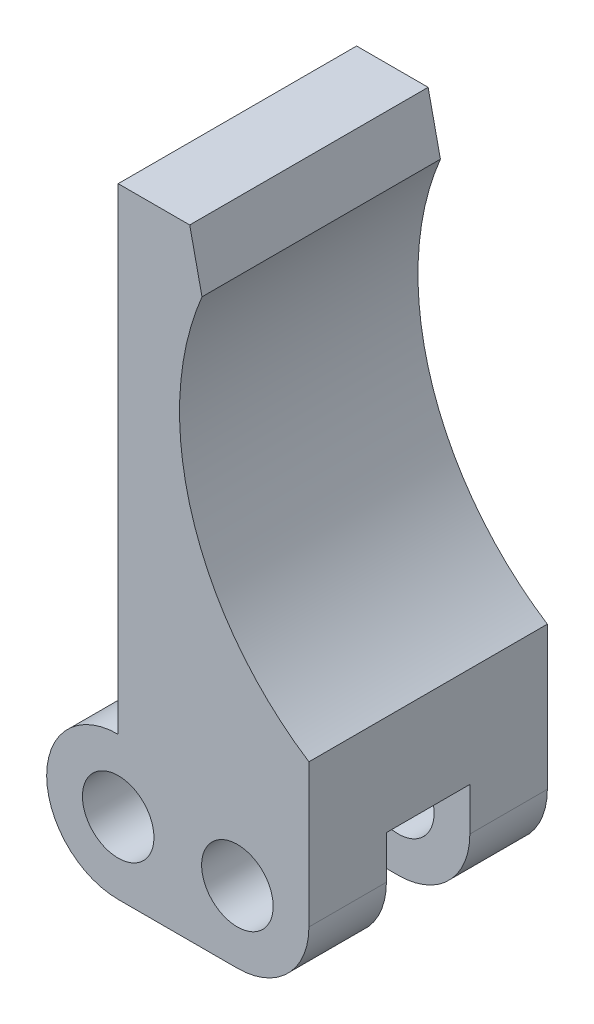
SolidWorks part; units mm, degrees
material "ABS"
ref_plane "Front Plane" through (0, 0, 0) normal (0, 0, 1) x (1, 0, 0)
ref_plane "Top Plane" through (0, 0, 0) normal (0, 1, 0) x (1, 0, 0)
ref_plane "Right Plane" through (0, 0, 0) normal (1, 0, 0) x (0, 0, -1)
sketch "Sketch1" plane through (0, 0, 0) normal (0, 0, 1) x (1, 0, 0)
  line L0 (0, -3) -> (5, -3)
  line L2 (0, 3) -> (0, 23)
  line L3 (8, 0) -> (8, 6)
  line L4 (0, 23) -> (3, 23)
  line L5 (3, 23) -> (3.5153, 20.6462)
  arc A0 (0, 3) -> (0, -3) centre (0, 0) ccw
  arc A1 (5, -3) -> (8, 0) centre (5, 0) ccw
  arc A2 (8, 6) -> (3.5153, 20.6462) centre (14.5, 16) cw
  circle A4 centre (0, 0) radius 1.5
  circle A5 centre (5, 0) radius 1.5
  dimension "D1" = 6
  dimension "D4" = 3
  dimension "D6" = 6
  dimension "D8" = 14.5
  dimension "D9" = 2.3538
  dimension "D2" = 20
  dimension "D3" = 3
  dimension "D5" = 5
  dimension "D7" = 16
extrude "Boss-Extrude1" add sketch "Sketch1" along normal mid plane 10
sketch "Sketch2" plane through (0, 0, 0) normal (0, 0, 1) x (1, 0, 0)
  line L0 (0, 3.5) -> (5, 3.5)
  line L3 (0, -3.5) -> (5, -3.5)
  circle A0 centre (0, 0) radius 1.5
  arc A1 (0, 3.5) -> (0, -3.5) centre (0, 0) ccw
  circle A2 centre (5, 0) radius 1.5
  arc A3 (5, -3.5) -> (5, 3.5) centre (5, 0) ccw
  dimension "D1" = 3
  dimension "D2" = 3.5
extrude "Cut-Extrude1" cut sketch "Sketch2" against normal mid plane 3.5
